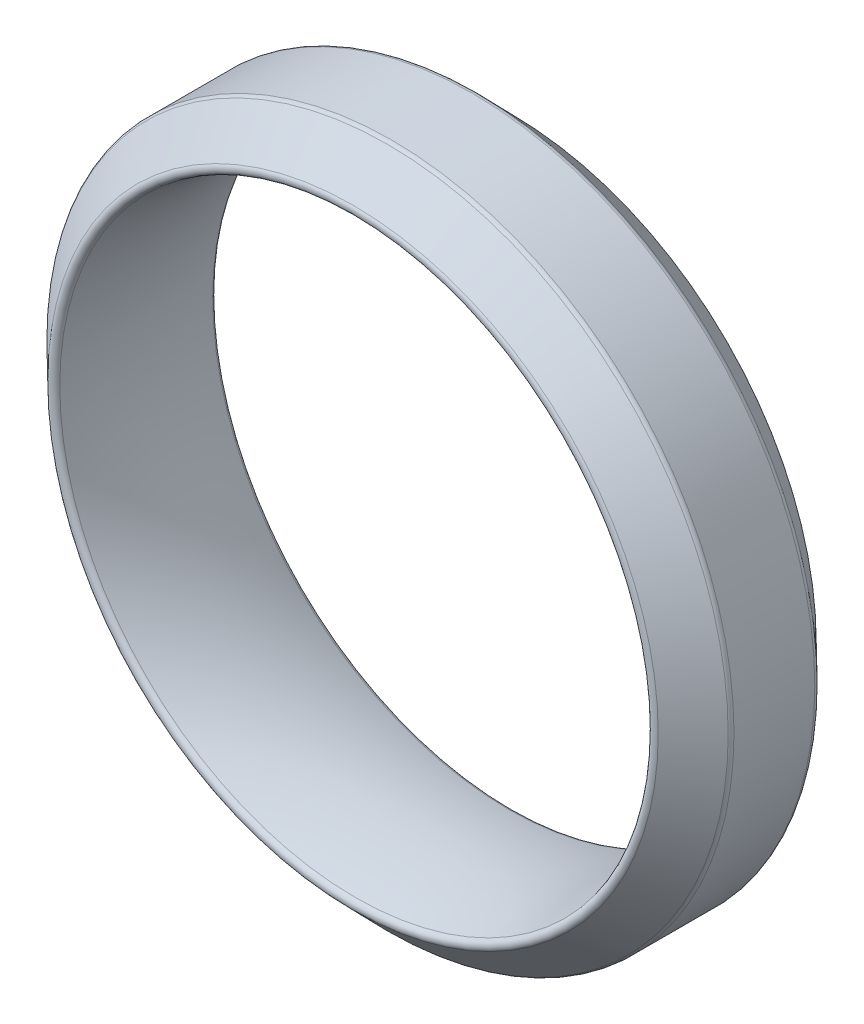
SolidWorks part; units mm, degrees
ref_plane "Front Plane" through (0, 0, 0) normal (0, 0, 1) x (1, 0, 0)
ref_plane "Top Plane" through (0, 0, 0) normal (0, 1, 0) x (1, 0, 0)
ref_plane "Right Plane" through (0, 0, 0) normal (1, 0, 0) x (0, 0, -1)
sketch "Sketch1" plane through (0, 0, 0) normal (1, 0, 0) x (0, 0, -1)
  line L0 (-3.81, 0.585) -> (-1.905, 2.54)
  line L1 (-1.905, 2.54) -> (1.905, 2.54)
  line L2 (1.905, 2.54) -> (3.81, 0.585)
  line L3 (0, 0) -> (0, 2.54) construction
  line L4 (-3.81, 0.585) -> (3.81, 0.585) construction
  arc A0 (-3.81, 0.585) -> (3.81, 0.585) centre (0, 12.7) ccw
  arc A1 (3.81, 0.585) -> (-3.81, 0.585) centre (0, 12.7) ccw construction
  dimension "D3" = 25.4
  dimension "D1" = 2.54
  dimension "D2" = 7.62
  dimension "D4" = 3.81
sketch "Sketch2" plane through (0, 0, 0) normal (1, 0, 0) x (0, 0, -1)
  line L0 (-24.8985, -12.7) -> (28.5731, -12.7)
  dimension "D1" = 12.7
revolve "Revolve1" add sketch "Sketch1" angle 360 about L0
fillet "Fillet1" radius 0.254 2 edges at (13.285, -12.7, -3.81) (13.285, -12.7, 3.81)
fillet "Fillet2" radius 0.254 2 edges at (15.24, -12.7, -1.905) (15.24, -12.7, 1.905)
